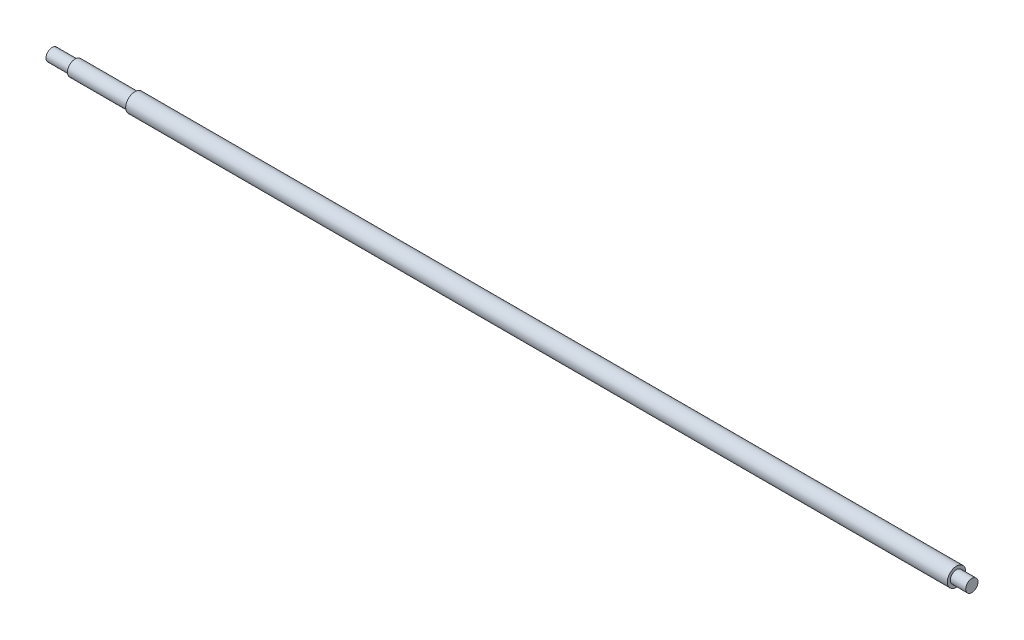
SolidWorks part; units mm, degrees
ref_plane "Front Plane" through (0, 0, 0) normal (0, 0, 1) x (1, 0, 0)
ref_plane "Top Plane" through (0, 0, 0) normal (0, 1, 0) x (1, 0, 0)
ref_plane "Right Plane" through (0, 0, 0) normal (1, 0, 0) x (0, 0, -1)
sketch "Sketch1" plane through (0, 0, 0) normal (0, 0, 1) x (1, 0, 0)
  line L0 (0, 0) -> (0, 4)
  line L1 (0, -55) -> (0, 55) construction
  line L2 (0, 4) -> (15, 4)
  line L3 (15, 4) -> (15, 5)
  line L4 (15, 5) -> (54, 5)
  line L5 (54, 5) -> (54, 6)
  line L6 (54, 6) -> (590, 6)
  line L7 (590, 6) -> (590, 4)
  line L8 (55, 0) -> (-55, 0) construction
  line L9 (600, 0) -> (0, 0) construction
  line L10 (590, 4) -> (600, 4)
  line L11 (600, 4) -> (600, 0)
  line L12 (0, 0) -> (600, 0)
  dimension "D1" = 8
  dimension "D2" = 10
  dimension "D3" = 12
  dimension "D4" = 8
  dimension "D5" = 10
  dimension "D6" = 15
  dimension "D7" = 39
  dimension "D8" = 600
revolve "Revolve1" add sketch "Sketch1" angle 360 about L9
